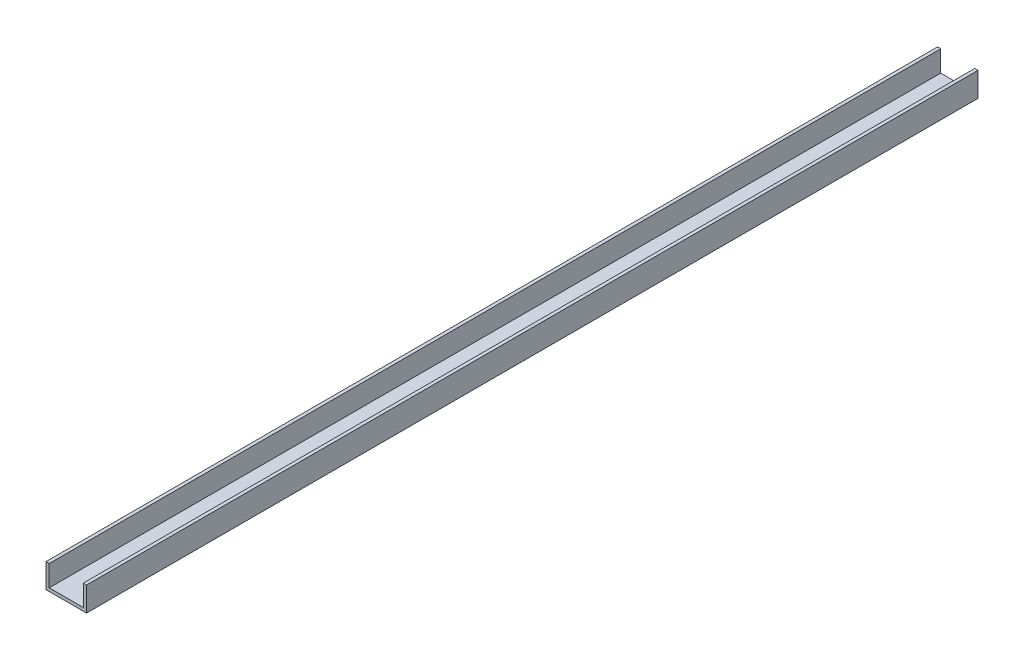
SolidWorks part; units mm, degrees
material "Alliage 1060"
ref_plane "Plan de face" through (0, 0, 0) normal (0, 0, 1) x (1, 0, 0)
ref_plane "Plan de dessus" through (0, 0, 0) normal (0, 1, 0) x (1, 0, 0)
ref_plane "Plan de droite" through (0, 0, 0) normal (1, 0, 0) x (0, 0, -1)
sketch "Esquisse1" plane through (0, 0, 0) normal (0, 0, 1) x (1, 0, 0)
  line L0 (-12.5, 0) -> (12.5, 0)
  line L1 (12.5, 0) -> (12.5, 15)
  line L2 (12.5, 15) -> (10.5, 15)
  line L3 (10.5, 15) -> (10.5, 2)
  line L4 (10.5, 2) -> (-10.5, 2)
  line L5 (0, 6.472) -> (0, -3.1073) construction
  line L6 (-10.5, 15) -> (-10.5, 2)
  line L7 (-12.5, 15) -> (-10.5, 15)
  line L8 (-12.5, 0) -> (-12.5, 15)
  point P10 (0, 2)
  point P13 (0, 0)
  dimension "D1" = 25
  dimension "D2" = 15
  dimension "D3" = 2
  dimension "D4" = 2
extrude "Boss.-Extru.1" add sketch "Esquisse1" along normal blind 550
